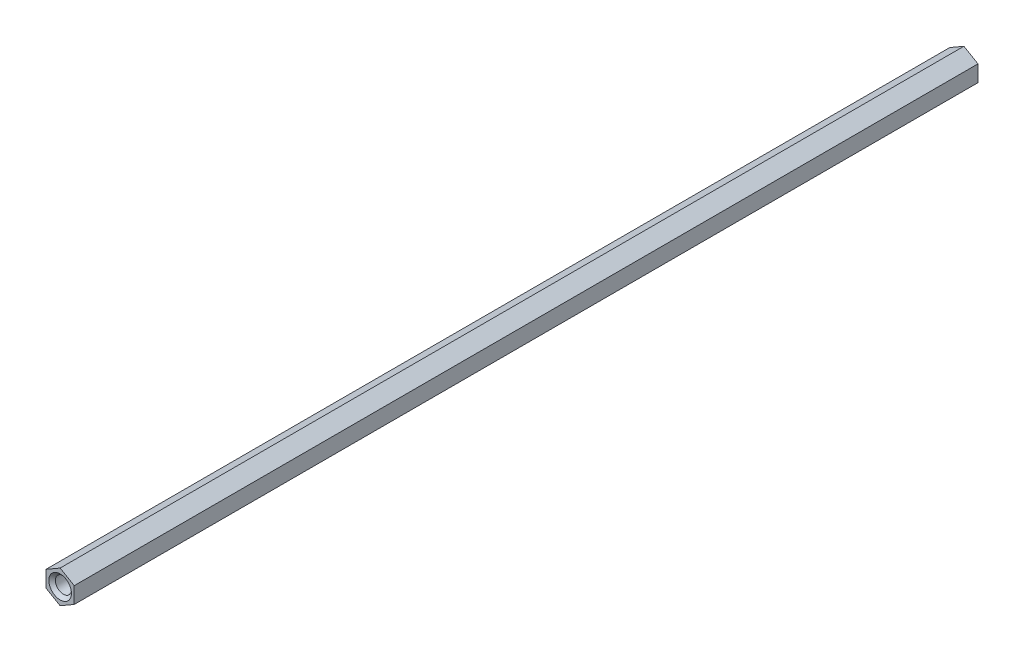
SolidWorks part; units mm, degrees
ref_plane "Front Plane" through (0, 0, 0) normal (0, 0, 1) x (1, 0, 0)
ref_plane "Top Plane" through (0, 0, 0) normal (0, 1, 0) x (1, 0, 0)
ref_plane "Right Plane" through (0, 0, 0) normal (1, 0, 0) x (0, 0, -1)
sketch "Sketch1" plane through (0, 0, 0) normal (0, 0, 1) x (1, 0, 0)
  line L0 (-4.7625, 0) -> (4.7625, 0) construction
  line L9 (0, 5.4993) -> (-4.7625, 2.7496) construction
  line L10 (-4.7625, 2.7496) -> (-4.7625, -2.7496) construction
  line L11 (-4.7625, -2.7496) -> (0, -5.4993) construction
  line L12 (0, -5.4993) -> (4.7625, -2.7496) construction
  line L13 (4.7625, -2.7496) -> (4.7625, 2.7496) construction
  line L14 (4.7625, 2.7496) -> (0, 5.4993) construction
  circle A3 centre (0, 0) radius 4.7625 construction
  point P4 (0, 0)
  dimension "Width" = 9.525
sketch "Sketch2" plane through (0, 0, 0) normal (1, 0, 0) x (0, 0, -1)
  line L0 (152.4, 5.4993) -> (-152.4, 5.4993) construction
  point P3 (-141.4462, 5.4993)
  point P4 (0, 5.4993)
  point P5 (141.4462, 5.4993)
  dimension "Length" = 304.8
  dimension "D1" = 10.9537
  dimension "D2" = 10.9537
sketch "Sketch3" plane through (0, 0, 0) normal (0, 0, 1) x (1, 0, 0)
  line L1 (0, 5.4993) -> (4.7625, 2.7496)
  line L2 (4.7625, 2.7496) -> (4.7625, -2.7496)
  line L3 (4.7625, -2.7496) -> (0, -5.4993)
  line L4 (0, -5.4993) -> (-4.7625, -2.7496)
  line L5 (-4.7625, -2.7496) -> (-4.7625, 2.7496)
  line L6 (-4.7625, 2.7496) -> (0, 5.4993)
extrude "Boss-Extrude1" add sketch "Sketch3" along normal mid plane 304.8
sketch "Sketch6" plane through (0, 0, 152.4) normal (0, 0, 1) x (1, 0, 0)
  point P0 (0, 0)
hole_wizard "1/4-28 Tapped Hole1" positions "Sketch6" profile "Sketch5" tap size "1/4-28" standard "ANSI Inch"
sketch "Sketch5" plane through (0, 0, 152.4) normal (1, 0, 0) x (0, -1, 0)
  line L0 (0, 0) -> (0, 16.8654)
  line L1 (0, 16.8654) -> (2.7051, 15.24)
  line L2 (2.7051, 15.24) -> (2.7051, 1.1049)
  line L3 (2.7051, 1.1049) -> (3.81, 0)
  line L5 (3.81, 0) -> (0, 0)
  line L6 (-2.7051, 1.1049) -> (-3.81, 0) construction
  line L10 (0, 16.8654) -> (-2.7051, 15.24) construction
  line L11 (0, -6.35) -> (0, 107.95) construction
  dimension "Tap Drill Dia." = 5.4102
  dimension "Tap Drill Depth" = 15.24
  dimension "Near C'Sink Dia." = 7.62
  dimension "Near C'Sink Angle" = 90
  dimension "Drill Angle" = 118
cosmetic thread "Hole Thread1" parameters "D1"=12.7, "D2"=6.35
sketch "Sketch9" plane through (0, 0, -152.4) normal (0, 0, -1) x (-1, 0, 0)
  point P0 (0, 0)
hole_wizard "1/4-28 Tapped Hole2" positions "Sketch9" profile "Sketch8" tap size "1/4-28" standard "ANSI Inch"
cosmetic thread "Hole Thread2" parameters "D1"=12.7, "D2"=6.35
sketch "Sketch8" plane through (0, 0, -152.4) normal (1, 0, 0) x (0, 1, 0)
  line L0 (0, 0) -> (0, 18.8593)
  line L1 (0, 18.8593) -> (2.7051, 17.2339)
  line L2 (2.7051, 17.2339) -> (2.7051, 1.1049)
  line L3 (2.7051, 1.1049) -> (3.81, 0)
  line L5 (3.81, 0) -> (0, 0)
  line L6 (-2.7051, 1.1049) -> (-3.81, 0) construction
  line L10 (0, 18.8593) -> (-2.7051, 17.2339) construction
  line L11 (0, -6.35) -> (0, 107.95) construction
  dimension "Tap Drill Dia." = 5.4102
  dimension "Tap Drill Depth" = 17.2339
  dimension "Near C'Sink Dia." = 7.62
  dimension "Near C'Sink Angle" = 90
  dimension "Drill Angle" = 118
equation "\"D1@Boss-Extrude1\" = \"Length@Sketch2\""
equation "\"D1@Sketch2\" = \"Width@Sketch1\" * 1.15"
equation "\"D2@Sketch2\"=\"D1@Sketch2\""
